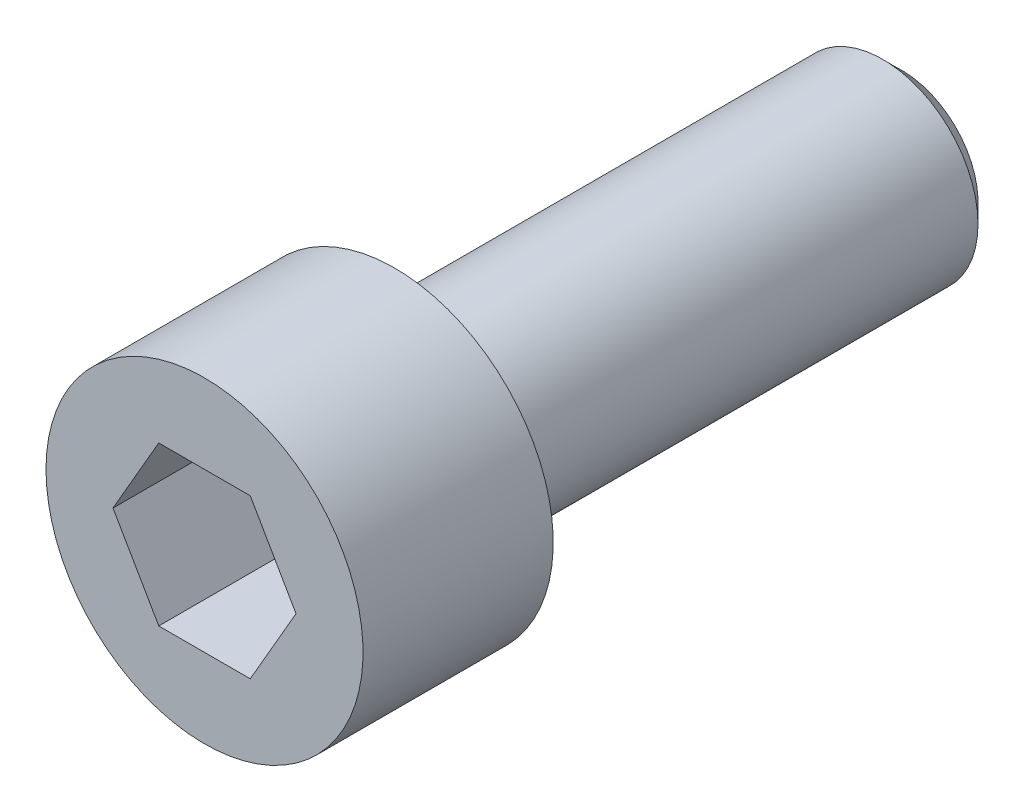
SolidWorks part; units mm, degrees
material "Простая углеродистая сталь"
ref_plane "Спереди" through (0, 0, 0) normal (0, 0, 1) x (1, 0, 0)
ref_plane "Сверху" through (0, 0, 0) normal (0, 1, 0) x (1, 0, 0)
ref_plane "Справа" through (0, 0, 0) normal (1, 0, 0) x (0, 0, -1)
sketch "Эскиз1" plane through (0, 0, 0) normal (1, 0, 0) x (0, 0, -1)
  line L0 (0, 0) -> (0, 2.5)
  line L1 (0, 2.5) -> (3, 2.5)
  line L2 (3, 2.5) -> (3, 1.5)
  line L3 (3, 1.5) -> (11, 1.5)
  line L4 (11, 1.5) -> (11, 0)
  line L5 (11, 0) -> (0, 0)
  line L6 (0, 0) -> (-1.7761, 0) construction
  dimension "D1" = 5
  dimension "D2" = 3
  dimension "D3" = 8
  dimension "D4" = 3
revolve "Повернуть1" add sketch "Эскиз1" angle 360 about L6
sketch "Эскиз2" plane through (0, 0, 0) normal (0, 0, 1) x (1, 0, 0)
  line L0 (0, 0) -> (0.8127, 0) construction
  line L1 (1.4434, 0) -> (0.7217, 1.25)
  line L2 (0.7217, 1.25) -> (-0.7217, 1.25)
  line L3 (-0.7217, 1.25) -> (-1.4434, 0)
  line L4 (-1.4434, 0) -> (-0.7217, -1.25)
  line L5 (-0.7217, -1.25) -> (0.7217, -1.25)
  line L6 (0.7217, -1.25) -> (1.4434, 0)
  circle A0 centre (0, 0) radius 1.25 construction
  dimension "D1" = 2.5
  dimension "D2" = 60
extrude "Вырез-Вытянуть1" cut sketch "Эскиз2" against normal blind 2
fillet "Скругление1" radius 0.3 1 edges at (-1.5, 0, -3)
chamfer "Фаска1" distance 0.3 angle 45 1 edges at (-1.5, 0, -11)
